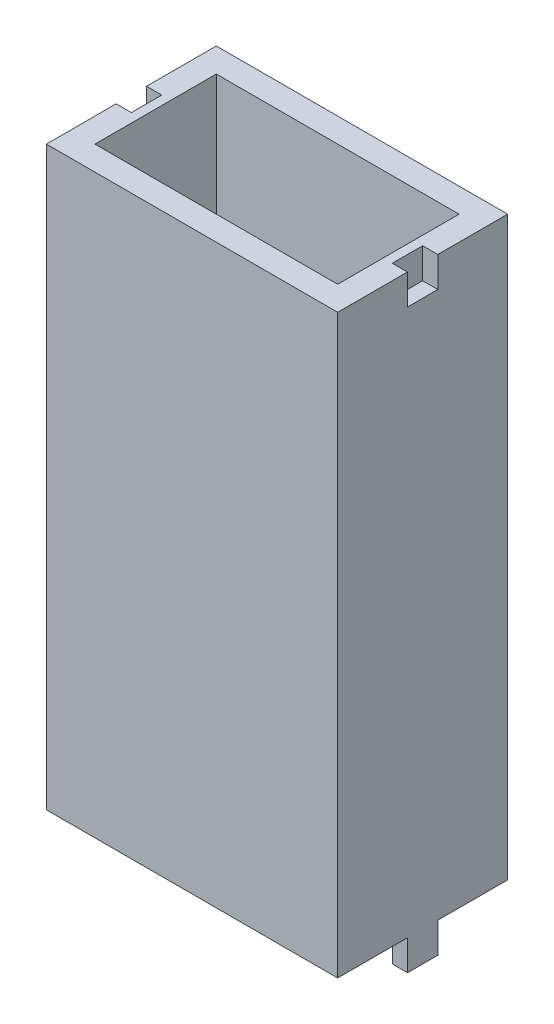
SolidWorks part; units mm, degrees
ref_plane "Front Plane" through (0, 0, 0) normal (0, 0, 1) x (1, 0, 0)
ref_plane "Top Plane" through (0, 0, 0) normal (0, 1, 0) x (1, 0, 0)
ref_plane "Right Plane" through (0, 0, 0) normal (1, 0, 0) x (0, 0, -1)
sketch "Sketch1" plane through (0, 0, 0) normal (0, 1, 0) x (1, 0, 0)
  line L0 (-4, 4) -> (44, 4)
  line L1 (0, 0) -> (40, 0)
  line L2 (0, 0) -> (0, -20)
  line L3 (0, -20) -> (40, -20)
  line L4 (40, 0) -> (40, -20)
  line L5 (44, 4) -> (44, -24)
  line L6 (-4, -24) -> (44, -24)
  line L7 (-4, 4) -> (-4, -24)
  dimension "D1" = 40
  dimension "D2" = 20
  dimension "D3" = 4
extrude "Boss-Extrude1" add sketch "Sketch1" along normal blind 95
sketch "Sketch2" plane through (0, 95, 0) normal (0, 1, 0) x (1, 0, 0)
  line L0 (-4, 4) -> (-4, -24) construction
  line L1 (-4, -7.5) -> (-1.5, -7.5)
  line L2 (-4, -7.5) -> (-4, -12.5)
  line L3 (-4, -12.5) -> (-1.5, -12.5)
  line L4 (-1.5, -7.5) -> (-1.5, -12.5)
  line L7 (41.5, -7.5) -> (44, -7.5)
  line L8 (41.5, -7.5) -> (41.5, -12.5)
  line L9 (41.5, -12.5) -> (44, -12.5)
  line L10 (44, -7.5) -> (44, -12.5)
  line L11 (44, 4) -> (44, -24) construction
  line L12 (-4, 4) -> (44, 4) construction
  point P18 (-4, -10)
  dimension "D1" = 14
  dimension "D2" = 5
  dimension "D3" = 2.5
  dimension "D4" = 2.5
extrude "Cut-Extrude1" cut sketch "Sketch2" against normal blind 5
sketch "Sketch6" plane through (0, 0, 0) normal (0, -1, 0) x (1, 0, 0)
  line L0 (-4, -4) -> (-4, 24) construction
  line L1 (-4, 12.5) -> (-1.5, 12.5)
  line L2 (-4, 12.5) -> (-4, 7.5)
  line L3 (-4, 7.5) -> (-1.5, 7.5)
  line L4 (-1.5, 12.5) -> (-1.5, 7.5)
  line L7 (41.5, 12.5) -> (44, 12.5)
  line L8 (41.5, 12.5) -> (41.5, 7.5)
  line L9 (41.5, 7.5) -> (44, 7.5)
  line L10 (44, 12.5) -> (44, 7.5)
  line L11 (44, -4) -> (44, 24) construction
  line L12 (-4, 24) -> (44, 24) construction
  point P18 (-4, 10)
  dimension "D1" = 14
  dimension "D2" = 5
  dimension "D3" = 2.5
  dimension "D4" = 2.5
extrude "Boss-Extrude3" add sketch "Sketch6" along normal blind 5
